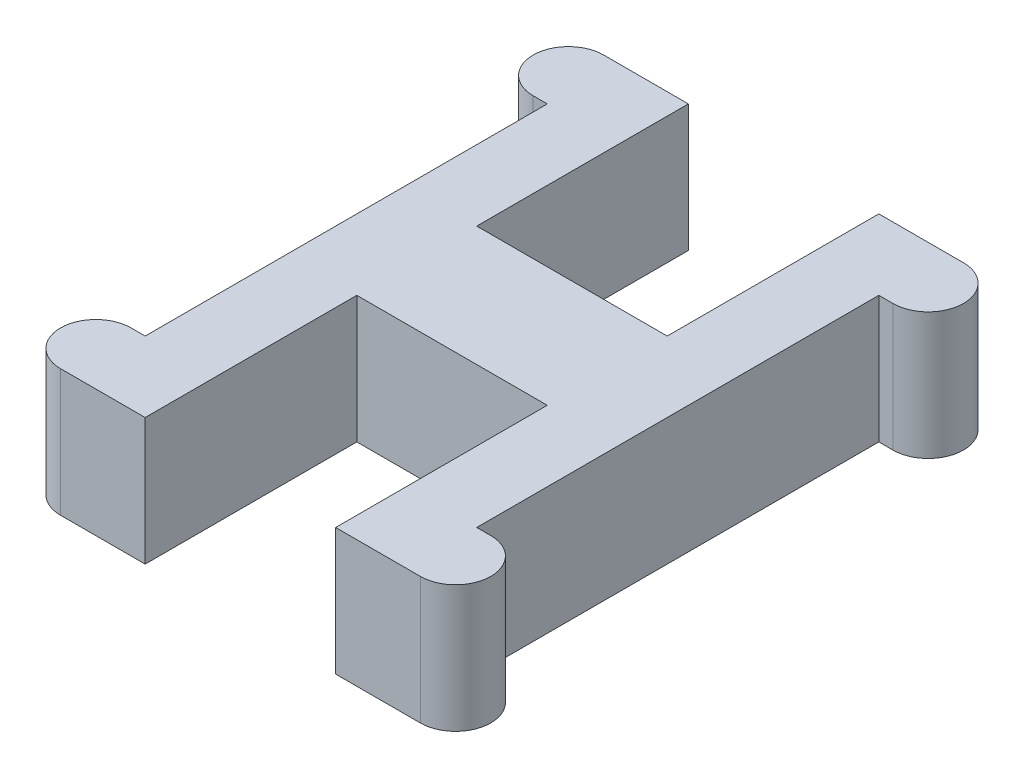
SolidWorks part; units mm, degrees
ref_plane "Front Plane" through (0, 0, 0) normal (0, 0, 1) x (1, 0, 0)
ref_plane "Top Plane" through (0, 0, 0) normal (0, 1, 0) x (1, 0, 0)
ref_plane "Right Plane" through (0, 0, 0) normal (1, 0, 0) x (0, 0, -1)
sketch "Sketch1" plane through (0, 0, 0) normal (0, 1, 0) x (1, 0, 0)
  line L0 (-2.55, 3.35) -> (2.55, 3.35) construction
  line L1 (-2.35, -3.85) -> (2.35, -3.85)
  line L2 (-2.35, -3.85) -> (-2.35, 3.85)
  line L3 (-2.35, 3.85) -> (2.35, 3.85)
  line L4 (2.35, -3.85) -> (2.35, 3.85)
  line L5 (-2.35, -3.85) -> (2.35, 3.85) construction
  line L6 (-2.35, 3.85) -> (2.35, -3.85) construction
  line L7 (-2.55, 3.85) -> (2.55, 3.85)
  line L8 (-2.55, 2.85) -> (2.55, 2.85)
  line L9 (-2.55, -3.35) -> (2.55, -3.35) construction
  line L10 (-2.55, -2.85) -> (2.55, -2.85)
  line L11 (-2.55, -3.85) -> (2.55, -3.85)
  line L13 (-1.35, 3.85) -> (1.35, 3.85)
  line L14 (-1.35, 3.85) -> (-1.35, 0.85)
  line L15 (-1.35, 0.85) -> (1.35, 0.85)
  line L16 (1.35, 3.85) -> (1.35, 0.85)
  line L17 (1.35, -3.85) -> (-1.35, -3.85)
  line L18 (1.35, -3.85) -> (1.35, -0.85)
  line L19 (1.35, -0.85) -> (-1.35, -0.85)
  line L20 (-1.35, -3.85) -> (-1.35, -0.85)
  arc A0 (-2.55, 3.85) -> (-2.55, 2.85) centre (-2.55, 3.35) ccw
  arc A1 (2.55, 2.85) -> (2.55, 3.85) centre (2.55, 3.35) ccw
  arc A2 (-2.55, -2.85) -> (-2.55, -3.85) centre (-2.55, -3.35) ccw
  arc A3 (2.55, -3.85) -> (2.55, -2.85) centre (2.55, -3.35) ccw
  point P0 (0, 0)
  point P8 (0, 3.35)
  point P15 (0, -3.35)
  point P28 (0, 0.85)
  point P29 (0, -0.85)
  point P30 (-2.35, 3.325)
  point P31 (-2.35, 3.325)
  point P32 (2.35, 3.325)
  point P33 (2.6329, 3.325)
  point P34 (-2.6944, 3.325)
  point P35 (0, 0)
  point P36 (0, 0)
  point P37 (2.51, -3.3302)
  point P38 (-2.7275, -3.3254)
  point P39 (0, 0)
  point P40 (0, 3.325)
  point P41 (0, -3.2971)
  point P42 (-2.8646, 3.325)
  dimension "D1" = 4.7
  dimension "D2" = 7.7
  dimension "D3" = 1
  dimension "D4" = 2.7
  dimension "D5" = 3
  dimension "D6" = 0.2
extrude "Boss-Extrude1" add sketch "Sketch1" along normal blind 1.8 contours L10 L20 L19 L18 L4 L8 L16 L15 L14 L2 | L14 L3 L2 L8 | L2 A0 | L3 L16 L8 L4 | L4 A1 | L4 A3 | L18 L1 L4 L10 | L1 L20 L10 L2 | L2 A2
